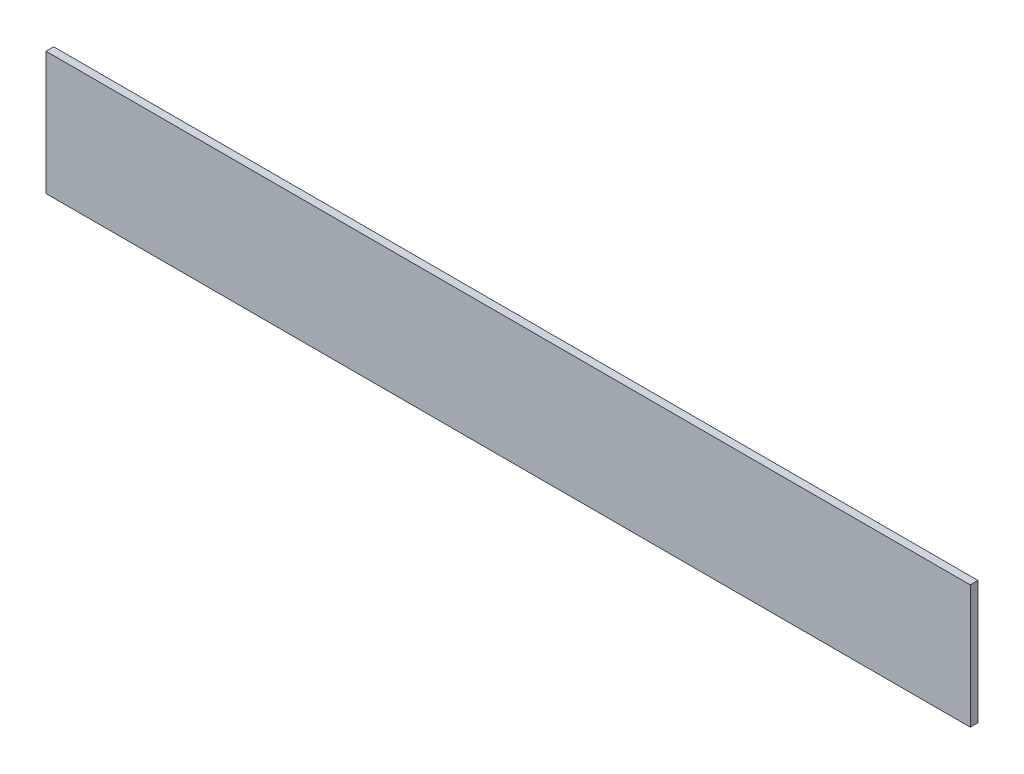
SolidWorks part; units mm, degrees
ref_plane "Front Plane" through (0, 0, 0) normal (0, 0, 1) x (1, 0, 0)
ref_plane "Top Plane" through (0, 0, 0) normal (0, 1, 0) x (1, 0, 0)
ref_plane "Right Plane" through (0, 0, 0) normal (1, 0, 0) x (0, 0, -1)
sketch "Sketch1" plane through (0, 0, 0) normal (0, 0, 1) x (1, 0, 0)
  line L1 (0, 0) -> (381, 0)
  line L2 (0, 0) -> (0, 50.8)
  line L3 (0, 50.8) -> (381, 50.8)
  line L4 (381, 0) -> (381, 50.8)
  dimension "D1" = 50.8
  dimension "D2" = 381
extrude "Boss-Extrude1" add sketch "Sketch1" along normal blind 3.175
